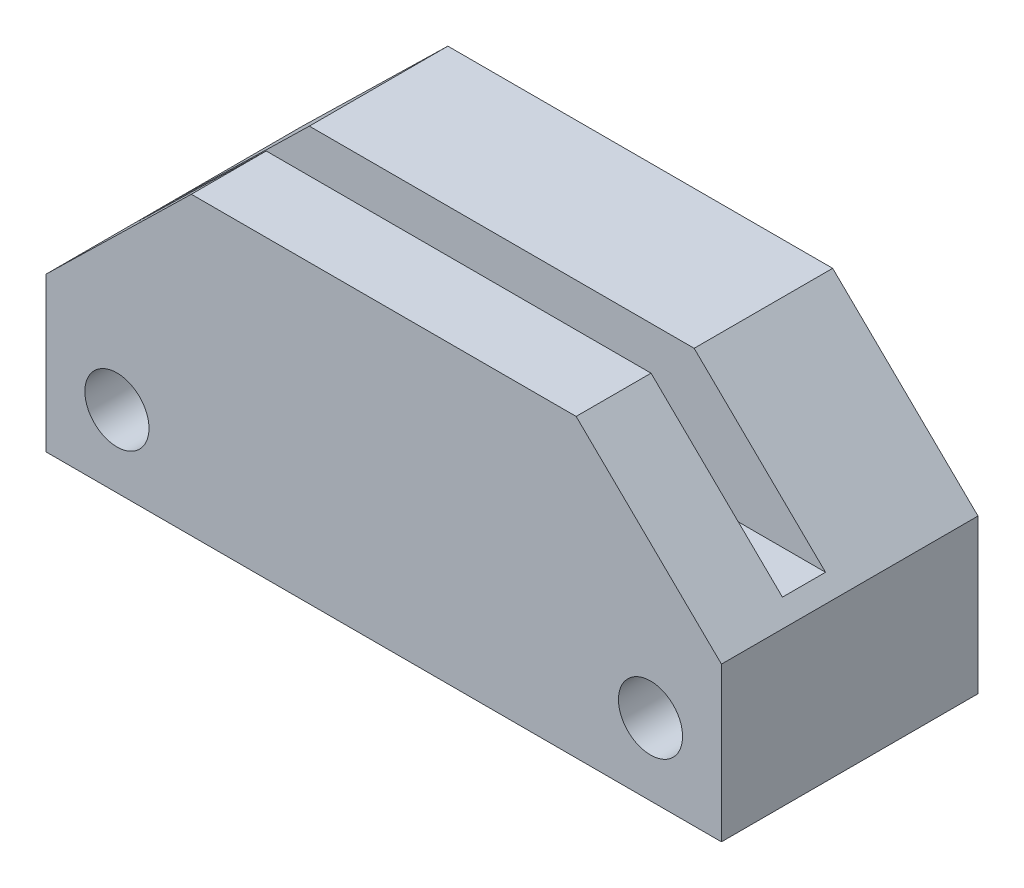
SolidWorks part; units mm, degrees
ref_plane "前视基准面" through (0, 0, 0) normal (0, 0, 1) x (1, 0, 0)
ref_plane "上视基准面" through (0, 0, 0) normal (0, 1, 0) x (1, 0, 0)
ref_plane "右视基准面" through (0, 0, 0) normal (1, 0, 0) x (0, 0, -1)
other "Configuration Table"
sketch "草图1" plane through (0, 0, 0) normal (0, 0, 1) x (1, 0, 0)
  line L0 (0, 0) -> (26.33, 0)
  line L1 (26.33, 0) -> (26.33, 6)
  line L2 (0, 0) -> (0, 6)
  line L3 (13.165, 0) -> (13.165, 14.7896) construction
  line L4 (5.665, 11.53) -> (20.665, 11.53)
  line L5 (0, 6) -> (5.665, 11.53)
  line L6 (20.665, 11.53) -> (26.33, 6)
  dimension "D1" = 26.33
  dimension "D2" = 6
  dimension "D3" = 6
  dimension "D4" = 15
  dimension "D5" = 7.5
  dimension "D6" = 11.53
extrude "凸台-拉伸1" add sketch "草图1" along normal blind 10
sketch "草图2" plane through (0, 11.53, 0) normal (0, 1, 0) x (1, 0, 0)
  line L0 (0, -10) -> (0, 0) construction
  line L1 (0, -5.4) -> (26.33, -5.4)
  line L2 (0, -5.4) -> (0, -7.08)
  line L3 (0, -7.08) -> (26.33, -7.08)
  line L4 (26.33, -5.4) -> (26.33, -7.08)
  line L5 (26.33, -10) -> (26.33, 0) construction
  line L6 (20.665, 0) -> (5.665, 0) construction
  line L7 (5.665, -10) -> (0, -10) construction
  dimension "D1" = 5.4
  dimension "D2" = 2.92
extrude "切除-拉伸1" cut sketch "草图2" against normal blind 5
sketch "草图3" plane through (0, 0, 0) normal (0, 0, -1) x (-1, 0, 0)
  line L0 (-13.165, 0) -> (-13.165, 11.53) construction
  line L1 (0, 0) -> (-26.33, 0) construction
  line L2 (-20.665, 11.53) -> (-5.665, 11.53) construction
  circle A0 centre (-23.565, 2.8) radius 1.25
  circle A1 centre (-2.765, 2.8) radius 1.25
  point P10 (0, 0)
  dimension "D3" = 2.5
  dimension "D4" = 2.5
  dimension "D1" = 20.8
  dimension "D2" = 10.4
  dimension "D5" = 2.8
extrude "切除-拉伸2" cut sketch "草图3" against normal up to next
